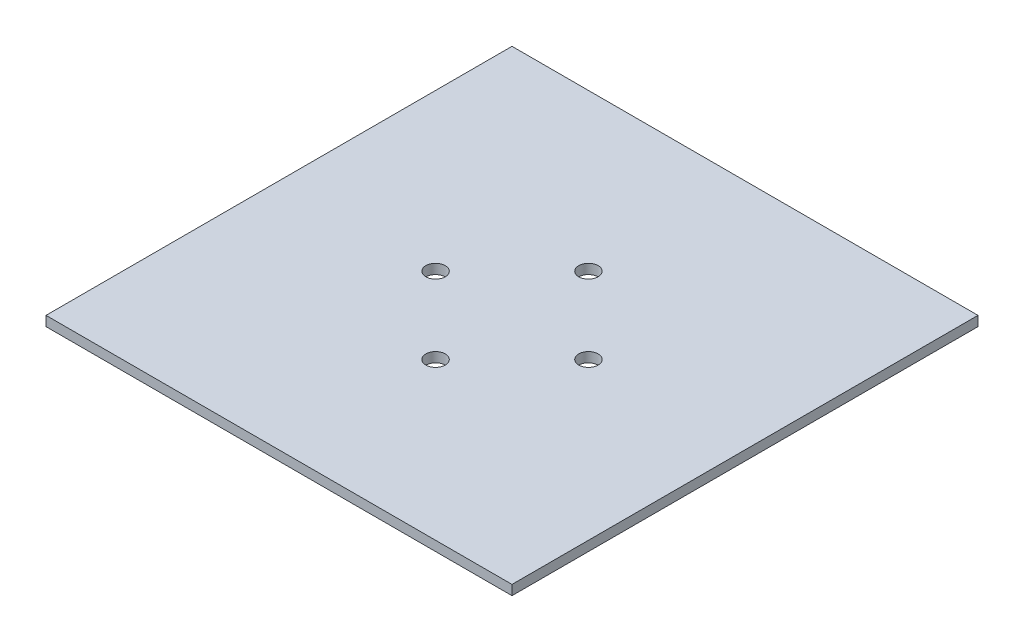
SolidWorks part; units mm, degrees
material "6061 Alloy"
ref_plane "Front Plane" through (0, 0, 0) normal (0, 0, 1) x (1, 0, 0)
ref_plane "Top Plane" through (0, 0, 0) normal (0, 1, 0) x (1, 0, 0)
ref_plane "Right Plane" through (0, 0, 0) normal (1, 0, 0) x (0, 0, -1)
sketch "Sketch1" plane through (0, 0, 0) normal (0, 1, 0) x (1, 0, 0)
  line L1 (-38.1, -38.1) -> (38.1, -38.1)
  line L2 (-38.1, -38.1) -> (-38.1, 38.1)
  line L3 (-38.1, 38.1) -> (38.1, 38.1)
  line L4 (38.1, -38.1) -> (38.1, 38.1)
  line L5 (-38.1, -38.1) -> (38.1, 38.1) construction
  line L6 (-38.1, 38.1) -> (38.1, -38.1) construction
  point P0 (0, 0)
  dimension "D1" = 76.2
extrude "Boss-Extrude1" add sketch "Sketch1" along normal blind 1.6002
hole_wizard "1/8 (0.125) Diameter Hole1" positions "Sketch3" profile "Sketch2" hole size "1/8" standard "ANSI Inch" end condition through all
sketch "Sketch3" plane through (0, 0, 0) normal (0, -1, 0) x (-1, 0, 0)
  line L0 (-12.5, 0) -> (12.5, 0) construction
  line L3 (0, 12.5) -> (0, -12.5) construction
  point P0 (0, 12.5)
  point P2 (0, -12.5)
  point P4 (12.5, 0)
  point P6 (-12.5, 0)
  dimension "D1" = 25
sketch "Sketch2" plane through (0, 0, -12.5) normal (1, 0, 0) x (0, 0, -1)
  line L0 (0, 0) -> (0, 1.6002)
  line L1 (0, 1.6002) -> (1.5875, 1.6002)
  line L2 (1.5875, 1.6002) -> (1.5875, 0)
  line L5 (1.5875, 0) -> (0, 0)
  line L11 (0, -6.35) -> (0, 107.95) construction
  dimension "Thru Hole Dia." = 3.175
  dimension "Thru Hole Depth" = 1.6002
